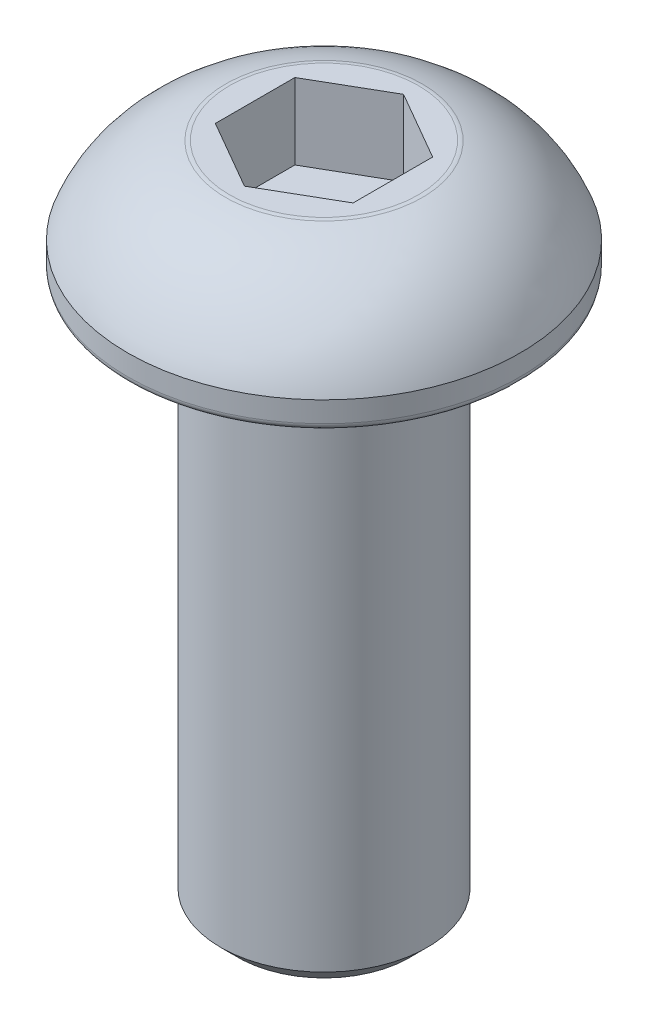
SolidWorks part; units mm, degrees
material "ASTM A36 Steel"
ref_plane "Front Plane" through (0, 0, 0) normal (0, 0, 1) x (1, 0, 0)
ref_plane "Top Plane" through (0, 0, 0) normal (0, 1, 0) x (1, 0, 0)
ref_plane "Right Plane" through (0, 0, 0) normal (1, 0, 0) x (0, 0, -1)
sketch "Sketch1" plane through (0, 0, 0) normal (0, 0, 1) x (1, 0, 0)
  line L7 (-1.5, -0.1) -> (-1.5, -7.75)
  line L8 (-1.25, -8) -> (0, -8)
  line L9 (0, -8) -> (0, 1.65)
  line L10 (-1.6, 0) -> (-2.75, 0)
  line L11 (-2.85, 0.1) -> (-2.85, 0.4)
  line L12 (-1.3725, 1.65) -> (0, 1.65)
  line L13 (-1.5, -7.75) -> (-1.25, -8)
  arc A0 (-2.85, 0.4) -> (-1.4287, 1.6436) centre (-0.9784, -0.3051) cw
  arc A3 (-2.75, 0) -> (-2.85, 0.1) centre (-2.75, 0.1) cw
  arc A4 (-1.4287, 1.6436) -> (-1.3725, 1.65) centre (-1.3725, 1.4) cw
  arc A5 (-1.5, -0.1) -> (-1.6, 0) centre (-1.6, -0.1) ccw
  point P1 (-1.5, -8)
  point P21 (-1.4, 1.65)
  point P24 (-1.5, 0)
  dimension "D1" = 1.5
  dimension "D7" = 2
  dimension "D8" = 0.1
  dimension "D9" = 0.25
  dimension "D10" = 0.1
  dimension "D2" = 2.85
  dimension "D4" = 1.4
  dimension "D5" = 1.65
  dimension "D6" = 0.4
  dimension "D11" = 8
revolve "Revolve1" add sketch "Sketch1" angle 360 about L9
sketch "Sketch2" plane through (0, 1.65, 0) normal (0, 1, 0) x (1, 0, 0)
  line L1 (-1, 0.5774) -> (-1, -0.5774)
  line L2 (-1, -0.5774) -> (0, -1.1547)
  line L3 (0, -1.1547) -> (1, -0.5774)
  line L4 (1, -0.5774) -> (1, 0.5774)
  line L5 (1, 0.5774) -> (0, 1.1547)
  line L6 (0, 1.1547) -> (-1, 0.5774)
  circle A0 centre (0, 0) radius 1 construction
  dimension "D1" = 2
extrude "Cut-Extrude1" cut sketch "Sketch2" against normal blind 1.1
